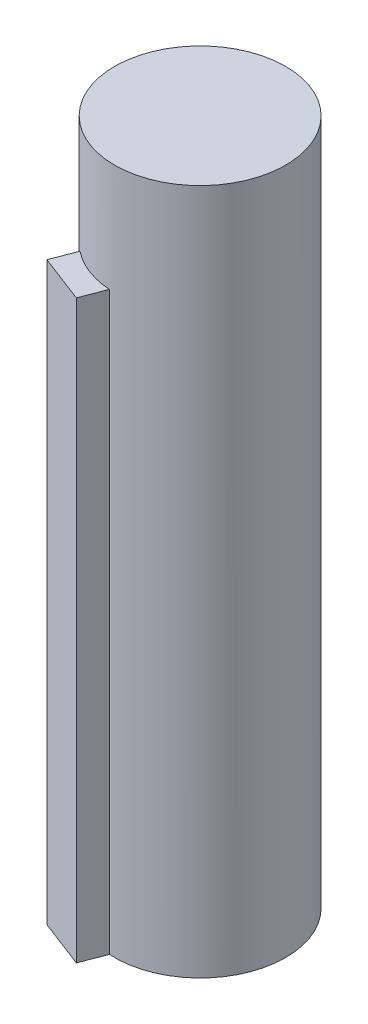
SolidWorks part; units mm, degrees
material "1023 Carbon Steel Sheet (SS)"
ref_plane "Front Plane" through (0, 0, 0) normal (0, 0, 1) x (1, 0, 0)
ref_plane "Top Plane" through (0, 0, 0) normal (0, 1, 0) x (1, 0, 0)
ref_plane "Right Plane" through (0, 0, 0) normal (1, 0, 0) x (0, 0, -1)
sketch "Sketch2" plane through (0, 0, 0) normal (0, 1, 0) x (1, 0, 0)
  line L0 (-0.8327, -13.3426) -> (-2.265, -17.0774)
  line L1 (-2.265, -17.0774) -> (-9.7346, -14.2129)
  line L2 (-9.7346, -14.2129) -> (-8.3023, -10.4781)
  arc A0 (-0.8327, -13.3426) -> (-8.3023, -10.4781) centre (0, 0) ccw
extrude "Boss-Extrude1" add sketch "Sketch2" along normal blind 90
sketch "Sketch3" plane through (0, 90, 0) normal (0, 1, 0) x (1, 0, 0)
  circle A0 centre (0, 0) radius 13.3686
extrude "Boss-Extrude2" add sketch "Sketch3" along normal blind 550
sketch "Sketch4" plane through (0, 640, 0) normal (0, 1, 0) x (1, 0, 0)
  circle A0 centre (0, 0) radius 30
extrude "Cut-Extrude1" cut sketch "Sketch4" against normal blind 532.76
